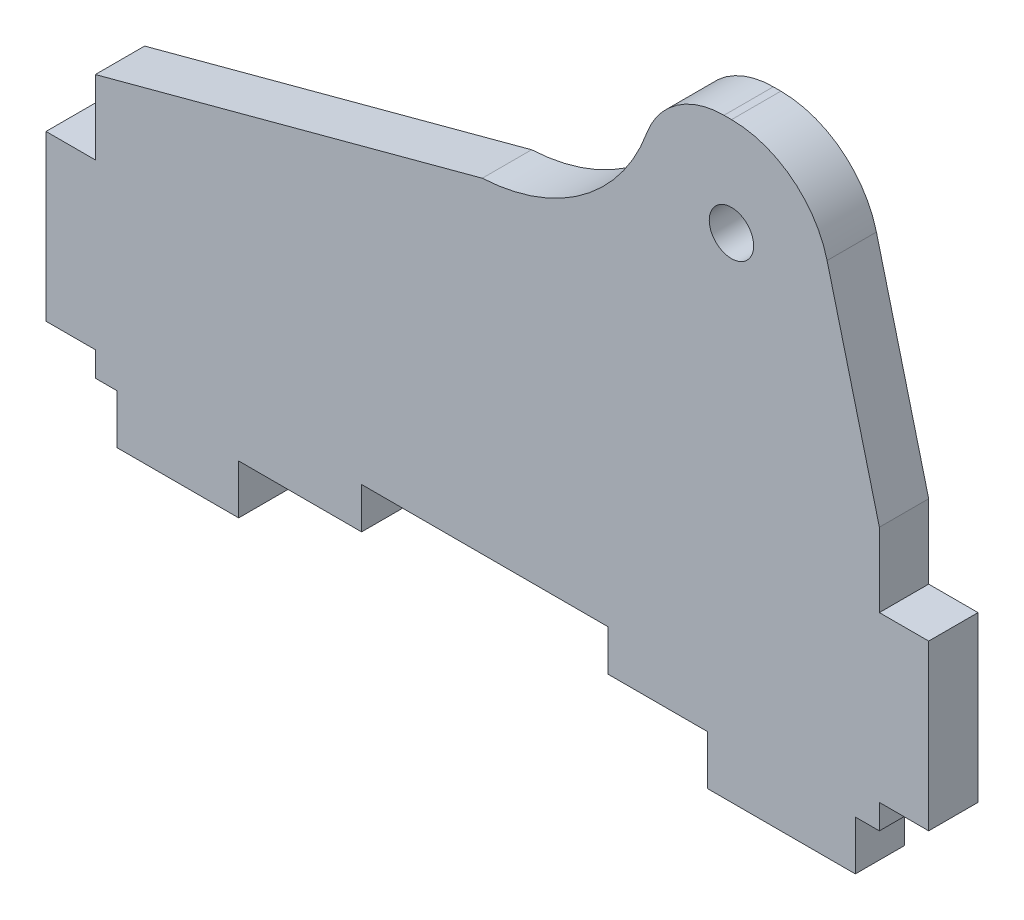
SolidWorks part; units mm, degrees
ref_plane "前视基准面" through (0, 0, 0) normal (0, 0, 1) x (1, 0, 0)
ref_plane "上视基准面" through (0, 0, 0) normal (0, 1, 0) x (1, 0, 0)
ref_plane "右视基准面" through (0, 0, 0) normal (1, 0, 0) x (0, 0, -1)
ref_plane "基准面1" through (0, 0, 0) normal (0, 0, -1) x (-1, 0, 0)
sketch "草图1" plane through (0, 0, 0) normal (0, 0, -1) x (-1, 0, 0)
  line L0 (-41.2462, 31.4756) -> (-41.7057, 31.4756)
  line L1 (-47.5193, 26.9593) -> (-50.6992, 14.4996)
  line L2 (-50.6992, 14.4996) -> (-50.6992, 10.0003)
  line L3 (-50.6992, 10.0003) -> (-53.6992, 10.0003)
  line L4 (-53.6992, 10.0003) -> (-53.6992, 0)
  line L5 (-53.6992, 0) -> (-50.6992, 0)
  line L6 (-50.6992, 0) -> (-50.6992, -1.5007)
  line L7 (-50.6992, -1.5007) -> (-49.2382, -1.5007)
  line L8 (-49.2382, -1.5007) -> (-49.2382, -4.5007)
  line L9 (-49.2382, -4.5007) -> (-40.2392, -4.5007)
  line L10 (-40.2392, -4.5007) -> (-40.2392, -1.4993)
  line L11 (-40.2392, -1.4993) -> (-34.2002, -1.4993)
  line L12 (-34.2002, -1.4993) -> (-34.2002, 1.0005)
  line L13 (-34.2002, 1.0005) -> (-19.2003, 1.0005)
  line L14 (-19.2003, 1.0005) -> (-19.2003, -1.4993)
  line L15 (-19.2003, -1.4993) -> (-11.7217, -1.4993)
  line L16 (-11.7217, -1.4993) -> (-11.7217, -4.5007)
  line L17 (-11.7217, -4.5007) -> (-4.3215, -4.5007)
  line L18 (-4.3215, -4.5007) -> (-4.3215, -1.5007)
  line L19 (-4.3215, -1.5007) -> (-3, -1.5007)
  line L20 (-3, -1.5007) -> (-3, 0)
  line L21 (-3, 0) -> (0, 0)
  line L22 (0, 0) -> (0, 10.0003)
  line L23 (0, 10.0003) -> (-3, 10.0003)
  line L24 (-3, 10.0003) -> (-3, 14.4996)
  line L25 (-3, 14.4996) -> (-26.5435, 20.8078)
  circle A0 centre (-41.6992, 25.4998) radius 1.35
  arc A1 (-41.7057, 31.4756) -> (-47.5193, 26.9593) centre (-41.7057, 25.4756) ccw
  arc A2 (-26.5435, 20.8078) -> (-36.5489, 28.1889) centre (-25.98, 32.0437) cw
  arc A3 (-36.5489, 28.1889) -> (-41.2462, 31.4756) centre (-41.2462, 26.4756) ccw
extrude "凸台-拉伸1" add sketch "草图1" against normal blind 3
